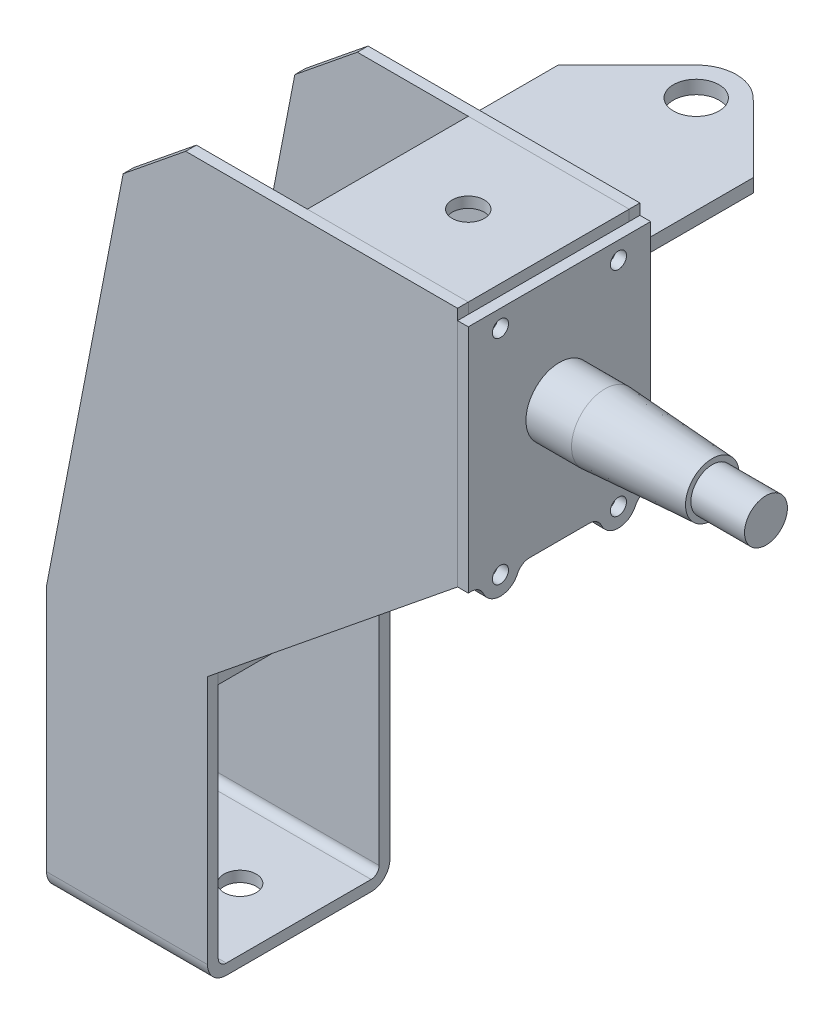
SolidWorks part; units mm, degrees
ref_plane "Front Plane" through (0, 0, 0) normal (0, 0, 1) x (1, 0, 0)
ref_plane "Top Plane" through (0, 0, 0) normal (0, 1, 0) x (1, 0, 0)
ref_plane "Right Plane" through (0, 0, 0) normal (1, 0, 0) x (0, 0, -1)
sketch "Sketch1" plane through (0, 0, 0) normal (0, 0, 1) x (1, 0, 0)
  line L0 (0, 0) -> (0, -100)
  line L1 (0, -2.2) -> (0, 2.2) construction
  line L2 (0, 0) -> (93.2275, 75.5556)
  line L3 (93.2275, 75.5556) -> (93.2275, 165.5556)
  line L4 (0, -100) -> (-60, -100)
  line L5 (-60, -100) -> (-60, -0.5906)
  line L6 (-60, -0.5906) -> (-31.4466, 146.6667)
  line L7 (-31.4466, 146.6667) -> (-8.1397, 165.5556)
  line L8 (-8.1397, 165.5556) -> (93.2275, 165.5556)
  point P0 (0, 0)
  dimension "D1" = 100
  dimension "D2" = 120
  dimension "D3" = 90
  dimension "D4" = 60
  dimension "D5" = 90
  dimension "D6" = 30
  dimension "D7" = 150
  dimension "D8" = 150
  dimension "D9" = 190
  dimension "D10" = 101.3672
  dimension "D11" = 129.023
  dimension "D12" = 99.4094
sketch "Sketch3" plane through (0, 0, 0) normal (1, 0, 0) x (0, 0, -1)
  line L2 (93.1124, 165.5556) -> (89.1124, 165.5556)
  line L3 (89.1124, 165.5556) -> (89.1124, -93)
  line L4 (86.1124, -96) -> (32.1124, -96)
  line L5 (0, 146.6667) -> (0, 165.5556) construction
  line L6 (0, 75.5556) -> (0, 165.5556) construction
  line L7 (0, -100) -> (0, -0.5906) construction
  line L8 (0, 84.2751) -> (0, -84.2751) construction
  line L9 (29.1124, -93) -> (29.1124, 165.5556)
  line L10 (29.1124, 165.5556) -> (25.1124, 165.5556)
  line L12 (93.1124, 161.5556) -> (93.1124, 161.5556)
  line L13 (93.1124, 165.5556) -> (93.1124, -93)
  line L14 (86.1124, -100) -> (32.1124, -100)
  line L15 (25.1124, -93) -> (25.1124, 168.1451)
  line L16 (25.1124, 161.5556) -> (25.1124, 161.5556)
  line L17 (93.1124, 161.5556) -> (93.1124, -93) construction
  line L18 (25.1124, -93) -> (25.1124, 161.5556) construction
  arc A0 (32.1124, -96) -> (29.1124, -93) centre (32.1124, -93) cw
  arc A1 (89.1124, -93) -> (86.1124, -96) centre (86.1124, -93) cw
  arc A2 (93.1124, -93) -> (86.1124, -100) centre (86.1124, -93) cw
  arc A3 (32.1124, -100) -> (25.1124, -93) centre (32.1124, -93) cw
  point P2 (0, 165.5556)
  point P7 (0, -100)
  point P20 (29.1124, -96)
  point P23 (89.1124, -96)
  dimension "D6" = 3
  dimension "D1" = 4
  dimension "D5" = 60
extrude "Boss-Extrude2" add sketch "Sketch3" along normal mid plane 214 contours A3 L14 A2 L13 L2 L3 A1 L4 A0 L9 L10 L15
sketch "Sketch4" plane through (0, 0, 0) normal (0, 0, 1) x (1, 0, 0)
  line L8 (-190, 11.8967) -> (-190, -230)
  line L9 (-190, -230) -> (130, -230)
  line L10 (130, -230) -> (130, -61.9751)
  line L11 (130, -61.9751) -> (223.2275, 13.5805)
  line L12 (223.2275, 13.5805) -> (223.2275, 295.5556)
  line L13 (223.2275, 295.5556) -> (-54.2043, 295.5556)
  line L14 (-54.2043, 295.5556) -> (-150.0618, 217.8685)
  line L15 (-150.0618, 217.8685) -> (-190, 11.8967)
  line L16 (-60, -0.5906) -> (-60, -100)
  line L17 (-60, -100) -> (0, -100)
  line L18 (0, -100) -> (0, 0)
  line L19 (0, 0) -> (93.2275, 75.5556)
  line L20 (93.2275, 75.5556) -> (93.2275, 165.5556)
  line L21 (93.2275, 165.5556) -> (-8.1397, 165.5556)
  line L22 (-8.1397, 165.5556) -> (-31.4466, 146.6667)
  line L23 (-31.4466, 146.6667) -> (-60, -0.5906)
  line L24 (-60, -0.5906) -> (-60, -100)
  line L25 (-60, -100) -> (0, -100)
  line L26 (0, -100) -> (0, 0)
  line L27 (0, 0) -> (93.2275, 75.5556)
  line L28 (93.2275, 75.5556) -> (93.2275, 165.5556)
  line L29 (93.2275, 165.5556) -> (-8.1397, 165.5556)
  line L30 (-8.1397, 165.5556) -> (-31.4466, 146.6667)
  line L31 (-31.4466, 146.6667) -> (-60, -0.5906)
  dimension "D1" = 0
  dimension "D2" = 130
extrude "Cut-Extrude1" cut sketch "Sketch4" against normal blind 214
sketch "Sketch5" plane through (0, 0, 0) normal (1, 0, 0) x (0, 0, -1)
  line L0 (89.1124, 0) -> (89.1124, -93) construction
  line L1 (29.1124, -0.5906) -> (89.1124, -0.5906)
  line L2 (29.1124, -0.5906) -> (29.1124, -4.5906)
  line L3 (29.1124, -4.5906) -> (89.1124, -4.5906)
  line L4 (89.1124, -0.5906) -> (89.1124, -4.5906)
  dimension "D1" = 4
  dimension "D2" = 60
extrude "Boss-Extrude3" add sketch "Sketch5" against normal blind 60 separate body
sketch "Sketch6" plane through (93.2275, 0, 0) normal (1, 0, 0) x (0, 0, -1)
  line L0 (89.1124, 165.5556) -> (89.1124, 75.5556) construction
  line L1 (29.1124, 165.5556) -> (89.1124, 165.5556)
  line L2 (29.1124, 165.5556) -> (29.1124, 161.5556)
  line L3 (29.1124, 161.5556) -> (89.1124, 161.5556)
  line L4 (89.1124, 165.5556) -> (89.1124, 161.5556)
  dimension "D1" = 4
extrude "Boss-Extrude4" add sketch "Sketch6" against normal blind 60 separate body
sketch "Sketch7" plane through (93.2275, 0, 0) normal (1, 0, 0) x (0, 0, -1)
  line L0 (25.1124, 161.5556) -> (93.1124, 161.5556)
  line L2 (25.1124, 161.5556) -> (25.1124, 75.5556)
  line L3 (25.1124, 75.5556) -> (26.2037, 75.5556)
  line L4 (93.1124, 161.5556) -> (93.1124, 75.5556)
  line L5 (29.1124, 0) -> (29.1124, 75.5556) construction
  line L6 (89.1124, 75.5556) -> (89.1124, 0) construction
  line L7 (29.1124, 75.5556) -> (29.1124, 165.5556) construction
  line L8 (89.1124, 165.5556) -> (89.1124, 75.5556) construction
  line L9 (48.0211, 75.5556) -> (70.2037, 75.5556)
  line L10 (92.0211, 75.5556) -> (93.1124, 75.5556)
  arc A0 (74.749, 72.6389) -> (87.4758, 72.6389) centre (81.1124, 75.5556) ccw
  arc A1 (30.749, 72.6389) -> (43.4758, 72.6389) centre (37.1124, 75.5556) ccw
  circle A2 centre (37.1124, 155.0821) radius 3
  circle A3 centre (81.1124, 155.0821) radius 3
  arc A4 (30.749, 72.6389) -> (26.2037, 75.5556) centre (26.2037, 70.5556) ccw
  arc A5 (43.4758, 72.6389) -> (48.0211, 75.5556) centre (48.0211, 70.5556) cw
  arc A6 (74.749, 72.6389) -> (70.2037, 75.5556) centre (70.2037, 70.5556) ccw
  arc A7 (87.4758, 72.6389) -> (92.0211, 75.5556) centre (92.0211, 70.5556) cw
  circle A8 centre (37.1124, 75.5556) radius 3
  circle A9 centre (81.1124, 75.5556) radius 3
  point P28 (44.1124, 75.5556)
  point P33 (88.1124, 75.5556)
  dimension "D1" = 14
  dimension "D2" = 14
  dimension "D3" = 6
  dimension "D4" = 6
  dimension "D5" = 8
  dimension "D6" = 8
  dimension "D7" = 79.5266
  dimension "D8" = 8
  dimension "D9" = 8
  dimension "D10" = 44
  dimension "D11" = 5
  dimension "D12" = 5
  dimension "D13" = 5
  dimension "D14" = 5
  dimension "D15" = 6
  dimension "D16" = 6
extrude "Boss-Extrude5" add sketch "Sketch7" along normal blind 4 separate body
sketch "Sketch8" plane through (0, 0, -93.1124) normal (0, 0, -1) x (-1, 0, 0)
  line L1 (12.1021, 115) -> (-60.6218, 115)
  line L2 (12.1021, 115) -> (12.1021, 120)
  line L3 (12.1021, 120) -> (-60.6218, 120)
  line L4 (-60.6218, 115) -> (-60.6218, 120)
  line L5 (12.1021, 117.5) -> (37.1021, 117.5)
  line L7 (60, -0.5906) -> (31.4466, 146.6667) construction
  point P8 (60, -0.5906)
  dimension "D1" = 5
  dimension "D2" = 115
  dimension "D3" = 130
  dimension "D4" = 167.0653
  dimension "D5" = 115.635
  dimension "D6" = 25
extrude "Boss-Extrude6" add sketch "Sketch8" along normal blind 100 separate body contours L4 L1 L2 L3
chamfer "Chamfer1" distance 25 angle 45 1 edges at (-12.1021, 117.5, -193.1124)
chamfer "Chamfer2" distance 25 angle 45 1 edges at (60.6218, 117.5, -193.1124)
sketch "Sketch9" plane through (0, 115, 0) normal (0, -1, 0) x (1, 0, 0)
  line L2 (93.2275, -93.1124) -> (0, -93.1124) construction
  line L3 (60.6218, -168.1124) -> (60.6218, -93.1124) construction
  circle A1 centre (24.2218, -183.1124) radius 15
  dimension "D1" = 30
  dimension "D3" = 36.4
  dimension "D2" = 90
extrude "Boss-Extrude7" add sketch "Sketch9" against normal blind 5
sketch "Sketch10" plane through (97.2275, 0, 0) normal (1, 0, 0) x (0, 0, -1)
  line L0 (25.1124, 165.5556) -> (93.1124, 75.5556)
  circle A0 centre (59.1124, 120.5556) radius 12.25
  dimension "D1" = 24.5
extrude "Cut-Extrude2" cut sketch "Sketch10" against normal blind 4
sketch "Sketch12" plane through (0, 165.5556, 0) normal (0, 1, 0) x (1, 0, 0)
  line L0 (33.2275, 89.1124) -> (93.2275, 29.1124)
  circle A0 centre (63.2275, 59.1124) radius 6
  dimension "D1" = 12
extrude "Cut-Extrude5" cut sketch "Sketch12" against normal blind 8 contours L0 A0 | L0 A0
sketch "Sketch13" plane through (0, -100, 0) normal (0, -1, 0) x (1, 0, 0)
  circle A0 centre (-23.1606, -60.4397) radius 6
extrude "Cut-Extrude6" cut sketch "Sketch13" against normal blind 10
sketch "Sketch15" plane through (93.2275, 0, 0) normal (-1, 0, 0) x (0, 0, 1)
  circle A0 centre (-59.1124, 120.5556) radius 15
  dimension "D1" = 30
extrude "Boss-Extrude8" add sketch "Sketch15" along normal blind 10 separate body
sketch "Sketch16" plane through (97.2275, 0, 0) normal (1, 0, 0) x (0, 0, -1)
  circle A0 centre (59.1124, 120.5556) radius 12.25
extrude "Boss-Extrude9" add sketch "Sketch16" against normal blind 10 separate body
sketch "Sketch17" plane through (97.2275, 0, 0) normal (1, 0, 0) x (0, 0, -1)
  circle A0 centre (59.1124, 120.5556) radius 12.5
  dimension "D1" = 25
extrude "Boss-Extrude10" add sketch "Sketch17" along normal blind 77 separate body
sketch "Sketch18" plane through (174.2275, 0, 0) normal (1, 0, 0) x (0, 0, -1)
  circle A0 centre (59.1124, 120.5556) radius 8
  circle A1 centre (59.1124, 120.5556) radius 12.5
  dimension "D1" = 16
  dimension "D2" = 25
extrude "Cut-Extrude7" cut sketch "Sketch18" against normal blind 20
chamfer "Chamfer3" distance 40 distance2 2.5 1 edges at (154.2275, 120.5556, -71.6124)
combine bodies "Combine1" operation type add bodies to combine 116 114 113
sketch "Sketch19" plane through (0, 115, 0) normal (0, -1, 0) x (1, 0, 0)
  circle A0 centre (24.2218, -183.1124) radius 8.5
  dimension "D1" = 17
extrude "Cut-Extrude8" cut sketch "Sketch19" against normal blind 20
